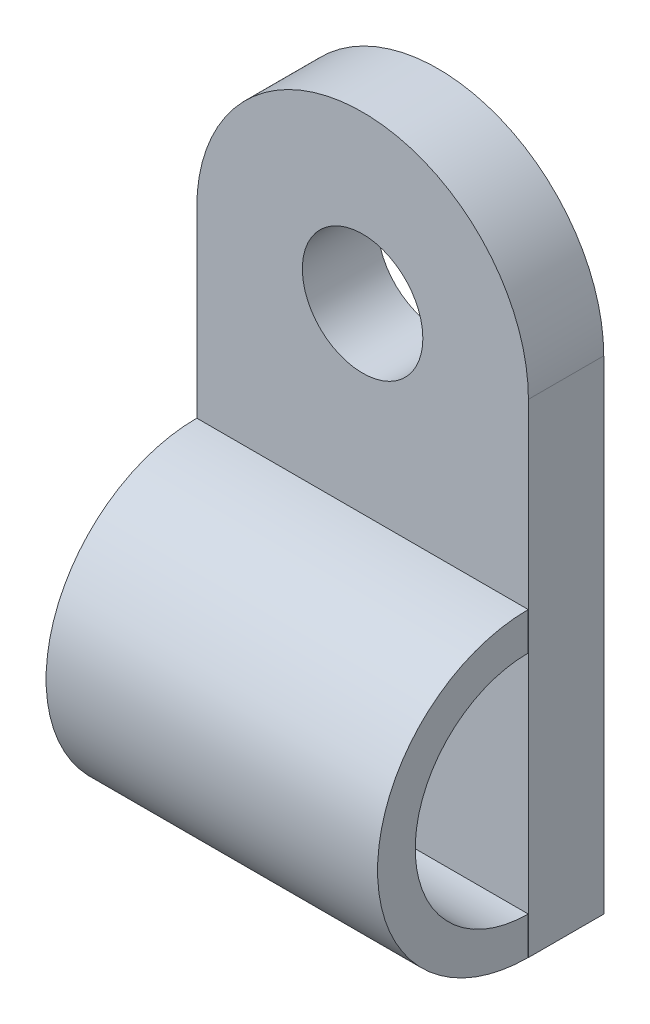
SolidWorks part; units mm, degrees
ref_plane "前视基准面" through (0, 0, 0) normal (0, 0, 1) x (1, 0, 0)
ref_plane "上视基准面" through (0, 0, 0) normal (0, 1, 0) x (1, 0, 0)
ref_plane "右视基准面" through (0, 0, 0) normal (1, 0, 0) x (0, 0, -1)
sketch "草图1" plane through (0, 0, 0) normal (0, 0, 1) x (1, 0, 0)
  line L0 (-4.4025, 0) -> (-4.4025, -12.8357)
  line L1 (4.4025, 0) -> (4.4025, -12.8357)
  line L2 (-4.4025, -12.8357) -> (4.4025, -12.8357)
  circle A0 centre (0, 0) radius 1.6
  circle A1 centre (0, 0) radius 4.4025
extrude "凸台-拉伸1" add sketch "草图1" along normal blind 2 contours A1 A0 | A1 L0 L2 L1
sketch "草图4" plane through (-4.4025, 0, 0) normal (-1, 0, 0) x (0, 0, 1)
  line L0 (2, 0) -> (2, -12.8357) construction
  line L1 (2, -12.8357) -> (0, -12.8357) construction
  line L2 (2, -4.8357) -> (2, -12.8357)
  circle A0 centre (2, -8.8357) radius 4
  circle A1 centre (2, -8.8357) radius 3
  line M3 (2, -12.8357) -> (2, 0)
  dimension "D1" = 4
extrude "凸台-拉伸4" add sketch "草图4" against normal blind 8.8 contours A1 A0 M3
